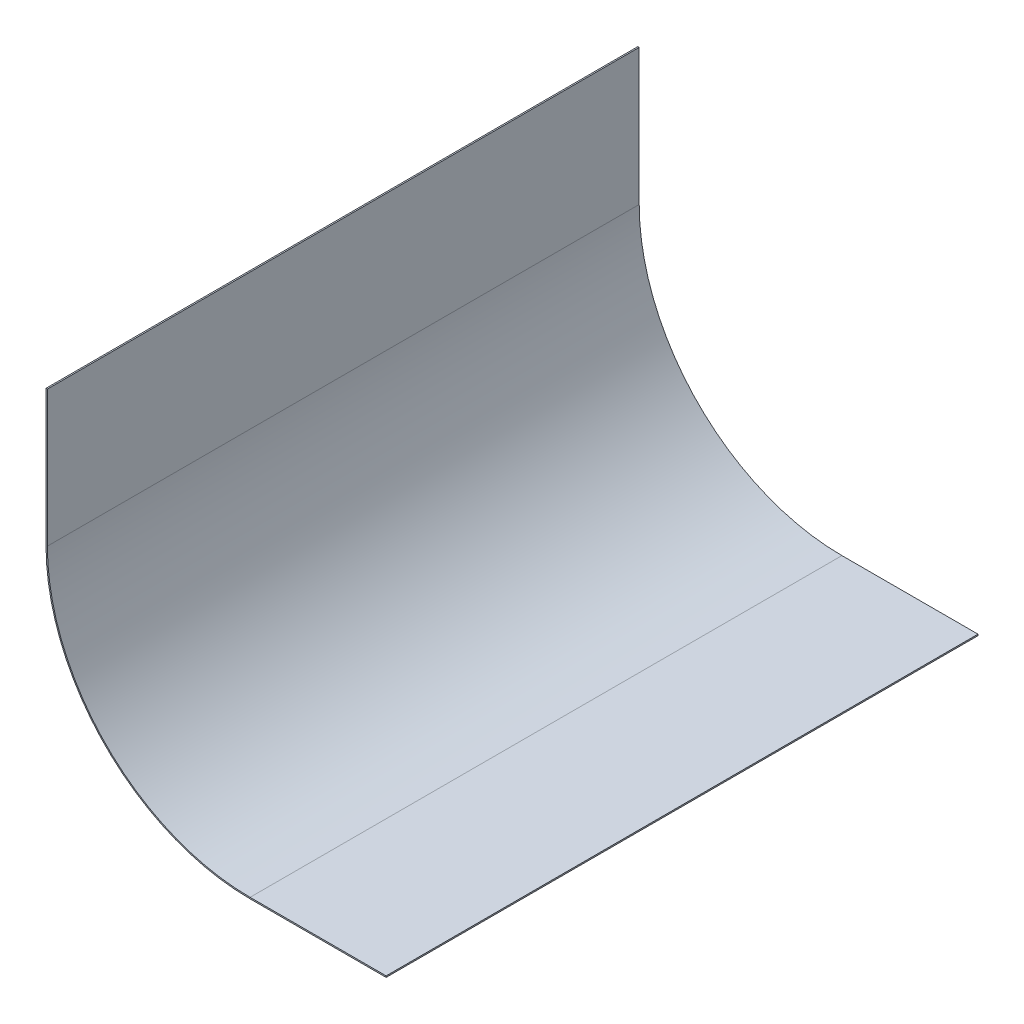
SolidWorks part; units mm, degrees
material "Acrylic (Medium-high impact)"
ref_plane "Front Plane" through (0, 0, 0) normal (0, 0, 1) x (1, 0, 0)
ref_plane "Top Plane" through (0, 0, 0) normal (0, 1, 0) x (1, 0, 0)
ref_plane "Right Plane" through (0, 0, 0) normal (1, 0, 0) x (0, 0, -1)
sketch "Sketch1" plane through (0, 0, 0) normal (0, 0, 1) x (1, 0, 0)
  line L0 (-42.8969, 250) -> (-42.8969, 150)
  line L1 (107.1031, 0) -> (207.1031, 0)
  line L2 (-41.8969, 250) -> (-41.8969, 150)
  line L3 (107.1031, 1) -> (207.1031, 1)
  line L4 (207.1031, 1) -> (207.1031, 0)
  line L5 (-41.8969, 250) -> (-42.8969, 250)
  arc A0 (107.1031, 0) -> (-42.8969, 150) centre (107.1031, 150) cw
  arc A1 (107.1031, 1) -> (-41.8969, 150) centre (107.1031, 150) cw
  point P6 (-42.8969, 0)
  dimension "D3" = 150
  dimension "D1" = 250
  dimension "D2" = 250
  dimension "D4" = 1
extrude "Boss-Extrude1" add sketch "Sketch1" along normal blind 490
sketch "Sketch3" plane through (0, 0, 490) normal (0, 0, 1) x (1, 0, 0)
  line L1 (-63.6798, 253.4196) -> (243.702, 253.4196)
  line L2 (-63.6798, 253.4196) -> (-63.6798, -23.3616)
  line L3 (-63.6798, -23.3616) -> (243.702, -23.3616)
  line L4 (243.702, 253.4196) -> (243.702, -23.3616)
extrude "Cut-Extrude1" cut sketch "Sketch3" against normal blind 55
